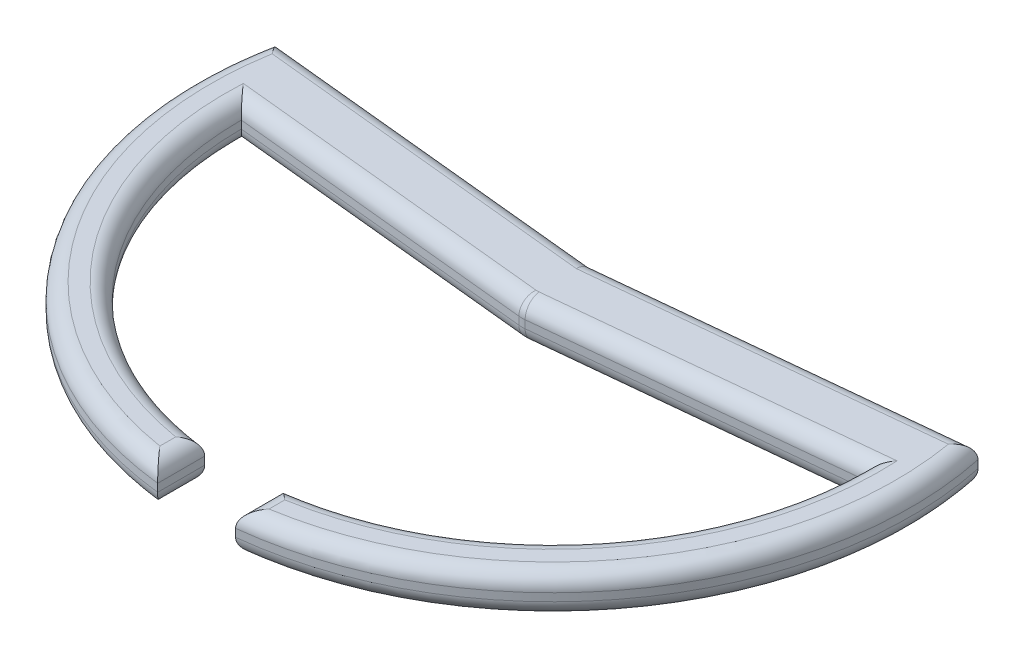
SolidWorks part; units mm, degrees
ref_plane "Front Plane" through (0, 0, 0) normal (0, 0, 1) x (1, 0, 0)
ref_plane "Top Plane" through (0, 0, 0) normal (0, 1, 0) x (1, 0, 0)
ref_plane "Right Plane" through (0, 0, 0) normal (1, 0, 0) x (0, 0, -1)
sketch "Sketch1" plane through (0, 0, 0) normal (0, 1, 0) x (1, 0, 0)
  line L0 (-0.4, -3.9799) -> (-40, 0)
  line L1 (0, 0) -> (0, 5) construction
  line L2 (0.4, -3.9799) -> (40, 0)
  line L5 (-5, -39.6863) -> (-5, -45.7275)
  line L6 (0, 5) -> (-45.0035, 9.523)
  line L7 (0, 5) -> (45.0035, 9.523)
  line L8 (5, -39.6863) -> (5, -45.7275)
  arc A1 (24.6848, -38.8157) -> (45.0035, 9.523) centre (0, 0) ccw
  arc A2 (-0.4, -3.9799) -> (0.4, -3.9799) centre (0, 0) ccw
  arc A3 (25.758, -30.6027) -> (40, 0) centre (0, 0) ccw
  arc A4 (-4, 0) -> (0, 4) centre (0, 0) ccw
  arc A5 (-40, 0) -> (-25.758, -30.6027) centre (0, 0) ccw
  arc A6 (-45.0035, 9.523) -> (-24.6848, -38.8157) centre (0, 0) ccw
  arc A7 (-45.0035, 9.523) -> (-5, -45.7275) centre (0, 0) ccw
  arc A8 (-40, 0) -> (-5, -39.6863) centre (0, 0) ccw
  arc A9 (5, -39.6863) -> (40, 0) centre (0, 0) ccw
  arc A10 (5, -45.7275) -> (45.0035, 9.523) centre (0, 0) ccw
  dimension "D1" = 10
  dimension "D2" = 92
  dimension "D3" = 4
  dimension "D4" = 8
  dimension "D6" = 40
  dimension "D5" = 5
extrude "Boss-Extrude1" add sketch "Sketch1" along normal mid plane 5
fillet "Fillet1" radius 2 22 edges at (20.2, -2.5, 1.99) (20.2, 2.5, 1.99) (30, 2.5, 26.4575) (30, -2.5, 26.4575) (5, -2.5, 42.7069) (5, 2.5, 42.7069) (37.2591, -2.5, 26.977) (37.2591, 2.5, 26.977) (22.5017, -2.5, -7.2615) (22.5017, 2.5, -7.2615) (-22.5017, -2.5, -7.2615) (-22.5017, 2.5, -7.2615) (-37.2591, -2.5, 26.977) (-37.2591, 2.5, 26.977) (-5, -2.5, 42.7069) (-5, 2.5, 42.7069) (-30, -2.5, 26.4575) (-30, 2.5, 26.4575) (-20.2, -2.5, 1.99) (-20.2, 2.5, 1.99) (0, -2.5, 4) (0, 2.5, 4)
